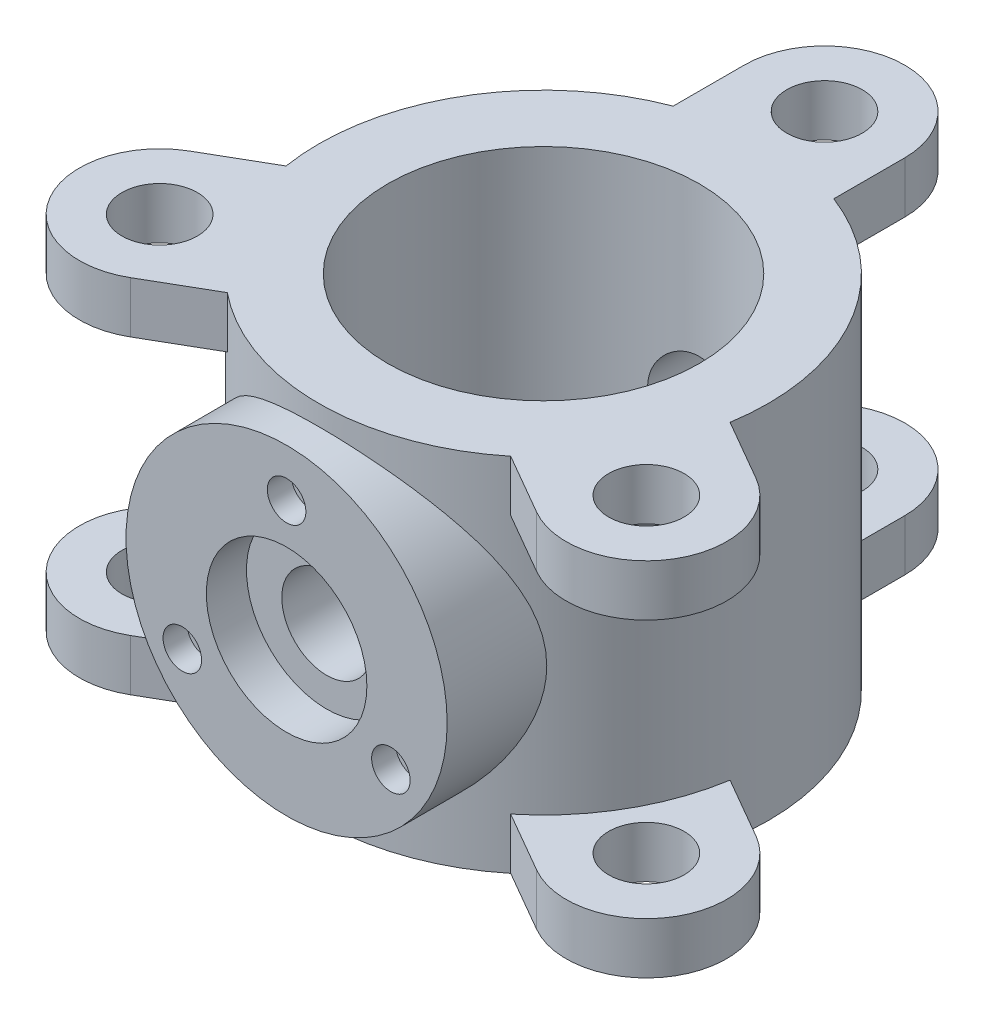
SolidWorks part; units mm, degrees
ref_plane "Front Plane" through (0, 0, 0) normal (0, 0, 1) x (1, 0, 0)
ref_plane "Top Plane" through (0, 0, 0) normal (0, 1, 0) x (1, 0, 0)
ref_plane "Right Plane" through (0, 0, 0) normal (1, 0, 0) x (0, 0, -1)
sketch "Sketch1" plane through (0, 0, 0) normal (0, 1, 0) x (1, 0, 0)
  circle A0 centre (0, 0) radius 140
  circle A1 centre (0, 0) radius 97
  dimension "D1" = 280
  dimension "D2" = 194
extrude "Boss-Extrude1" add sketch "Sketch1" along normal blind 225
sketch "Sketch2" plane through (0, 225, 0) normal (0, 1, 0) x (1, 0, 0)
  line L1 (-50, 175) -> (50, 175) construction
  line L2 (-50, 175) -> (-50, 114.8965)
  line L3 (-50, 114.8965) -> (50, 114.8965)
  line L4 (50, 175) -> (50, 114.8965)
  line L5 (-50, 175) -> (50, 114.8965) construction
  line L6 (-50, 114.8965) -> (50, 175) construction
  arc A0 (50, 175) -> (-50, 175) centre (0, 175) ccw
  circle A1 centre (0, 175) radius 23.5
  point P0 (0, 144.9482)
  dimension "D2" = 100
  dimension "D3" = 47
  dimension "D1" = 175
extrude "Boss-Extrude2" add sketch "Sketch2" against normal blind 32
pattern_circular "CirPattern1" count 3 over 360 about axis through (0, 0, 0) along (0, 1, 0) of "Boss-Extrude2"
ref_plane "Plane1" through (0, 112.5, 0) normal (0, 1, 0) x (1, 0, 0)
mirror "Mirror1" about plane through (0, 112.5, 0) normal (0, 1, 0) of "CirPattern1", "Boss-Extrude2"
ref_plane "Plane2" through (0, 0, 160) normal (0, 0, 1) x (1, 0, 0)
sketch "Sketch3" plane through (0, 0, 160) normal (0, 0, 1) x (1, 0, 0)
  circle A0 centre (0, 112.5) radius 100
  dimension "D1" = 200
  dimension "D2" = 112.5
extrude "Boss-Extrude3" add sketch "Sketch3" against normal up to next
sketch "Sketch4" plane through (0, 0, 160) normal (0, 0, 1) x (1, 0, 0)
  circle A0 centre (0, 107.598) radius 50
  dimension "D1" = 100
extrude "Cut-Extrude1" cut sketch "Sketch4" against normal blind 25
sketch "Sketch5" plane through (0, 0, 135) normal (0, 0, 1) x (1, 0, 0)
  circle A0 centre (0, 103.8222) radius 28
  dimension "D1" = 56
extrude "Cut-Extrude2" cut sketch "Sketch5" against normal through all
sketch "Sketch6" plane through (0, 0, 160) normal (0, 0, 1) x (1, 0, 0)
  circle A0 centre (0, 182.598) radius 12
  circle A1 centre (0, 107.598) radius 50 construction
  point P2 (0, 0)
  point P3 (0, 0)
  point P6 (0, 0)
  point P8 (0, 0)
  point P9 (0, 0)
  dimension "D1" = 24
  dimension "D2" = 75
extrude "Cut-Extrude3" cut sketch "Sketch6" against normal blind 15
pattern_circular "CirPattern2" count 3 over 360 about axis through (0, 107.598, 0) along (0, 0, 1) of "Cut-Extrude3"
